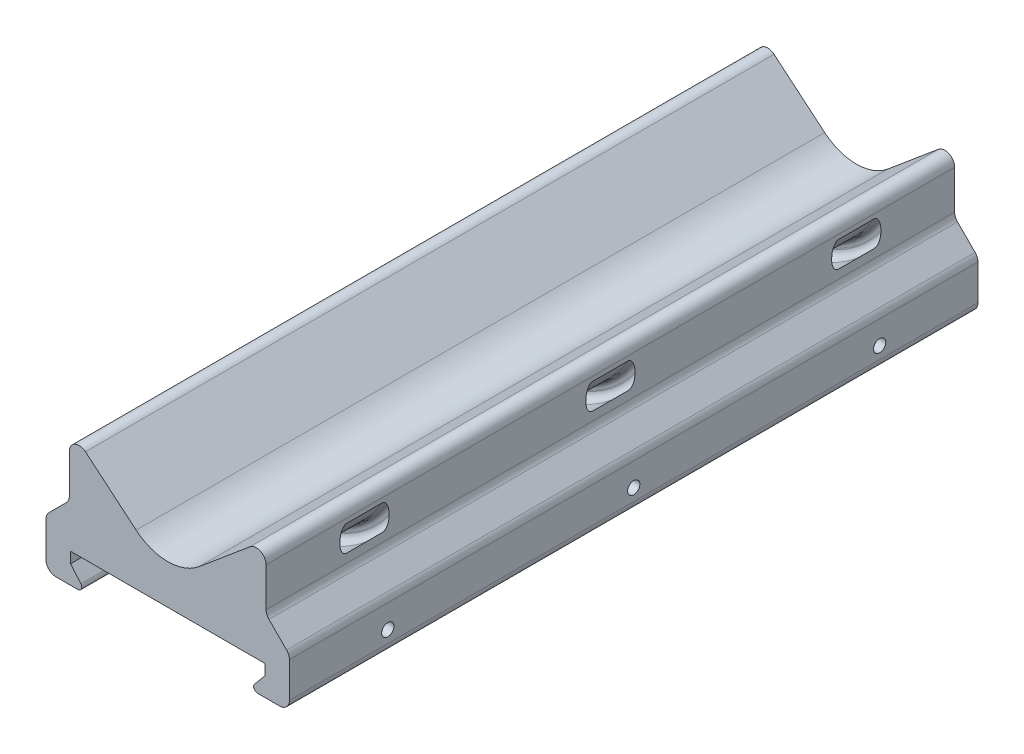
SolidWorks part; units mm, degrees
ref_plane "Front Plane" through (0, 0, 0) normal (0, 0, 1) x (1, 0, 0)
ref_plane "Top Plane" through (0, 0, 0) normal (0, 1, 0) x (1, 0, 0)
ref_plane "Right Plane" through (0, 0, 0) normal (1, 0, 0) x (0, 0, -1)
sketch "Sketch1" plane through (0, 0, 0) normal (0, 0, 1) x (1, 0, 0)
  line L0 (0, 15.6125) -> (0, -8.5333) construction
  line L1 (6.4279, 10.3936) -> (16.7144, 19.0251)
  line L2 (20, 17.493) -> (20, 9.5784)
  line L3 (20.5858, 8.1642) -> (24.1642, 4.5858)
  line L4 (24.75, 3.1716) -> (24.75, -4)
  line L5 (22.75, -6) -> (18.277, -6)
  line L7 (19.75, 0) -> (-19.75, 0)
  line L9 (-22.75, -6) -> (-18.277, -6)
  line L10 (-24.75, 3.1716) -> (-24.75, -4)
  line L11 (-20.5858, 8.1642) -> (-24.1642, 4.5858)
  line L12 (-20, 17.493) -> (-20, 9.5784)
  line L13 (-6.4279, 10.3936) -> (-16.7144, 19.0251)
  line L14 (-19.05, -0.1) -> (19.05, -0.1) construction
  line L15 (19.05, -0.1) -> (19.05, -2.1) construction
  line L16 (19.05, -2.1) -> (13.05, -8.1) construction
  line L17 (13.05, -8.1) -> (-13.05, -8.1) construction
  line L18 (-13.05, -8.1) -> (-19.05, -2.1) construction
  line L19 (-19.05, -0.1) -> (-19.05, -2.1) construction
  line L20 (17.6642, -4.6858) -> (19.75, -2.2)
  line L21 (19.75, -2.2) -> (19.75, 0)
  line L22 (-19.75, -2.2) -> (-19.75, 0)
  line L23 (-17.6642, -4.6858) -> (-19.75, -2.2)
  arc A0 (-6.4279, 10.3936) -> (6.4279, 10.3936) centre (0, 18.0541) ccw
  arc A1 (20, 9.5784) -> (20.5858, 8.1642) centre (22, 9.5784) ccw
  arc A2 (24.1642, 4.5858) -> (24.75, 3.1716) centre (22.75, 3.1716) cw
  arc A3 (24.75, -4) -> (22.75, -6) centre (22.75, -4) cw
  arc A4 (-22.75, -6) -> (-24.75, -4) centre (-22.75, -4) cw
  arc A5 (-24.75, 3.1716) -> (-24.1642, 4.5858) centre (-22.75, 3.1716) cw
  arc A6 (-20.5858, 8.1642) -> (-20, 9.5784) centre (-22, 9.5784) ccw
  arc A7 (16.7144, 19.0251) -> (20, 17.493) centre (18, 17.493) cw
  arc A8 (-20, 17.493) -> (-16.7144, 19.0251) centre (-18, 17.493) cw
  arc A9 (18.277, -6) -> (17.6642, -4.6858) centre (18.277, -5.2) cw
  arc A10 (-17.6642, -4.6858) -> (-18.277, -6) centre (-18.277, -5.2) cw
  point P11 (0, 0)
  point P19 (0, 5)
  point P22 (20, 8.75)
  point P25 (24.75, 4)
  point P28 (24.75, -6)
  point P31 (-24.75, -6)
  point P34 (-24.75, 4)
  point P37 (-20, 8.75)
  point P40 (20, 21.782)
  point P43 (-20, 21.782)
  point P51 (0, -8.1)
  point P52 (0, -0.1)
  point P56 (16.5614, -6)
  point P59 (-16.5614, -6)
  dimension "D10" = 10
  dimension "D11" = 2
  dimension "D18" = 0.8
  dimension "D1" = 19.75
  dimension "D2" = 5
  dimension "D3" = 20
  dimension "D4" = 135
  dimension "D5" = 50
  dimension "D6" = 6
  dimension "D7" = 4
  dimension "D8" = 50
  dimension "D9" = 5
  dimension "D12" = 38.1
  dimension "D13" = 135
  dimension "D14" = 8
  dimension "D15" = 2
  dimension "D16" = 0.2
  dimension "D17" = 2.2
extrude "Boss-Extrude1" add sketch "Sketch1" along normal blind 140
sketch "Sketch2" plane through (0, 0, 0) normal (1, 0, 0) x (0, 0, -1)
  line L0 (-140, 0) -> (0, 0) construction
  line L1 (-15, 5) -> (-25, 5)
  line L2 (-15, 5) -> (-15, 2)
  line L3 (-15, 2) -> (-25, 2)
  line L4 (-25, 5) -> (-25, 2)
  line L5 (0, 4.5858) -> (0, 8.1642) construction
  line L6 (-65, 5) -> (-75, 5)
  line L7 (-65, 5) -> (-65, 2)
  line L8 (-65, 2) -> (-75, 2)
  line L9 (-75, 5) -> (-75, 2)
  line L10 (-115, 5) -> (-125, 5)
  line L11 (-115, 5) -> (-115, 2)
  line L12 (-115, 2) -> (-125, 2)
  line L13 (-125, 5) -> (-125, 2)
  line L14 (-129.3538, 28.0541) -> (-44.4002, 28.0541) construction
  line L15 (-140, 8.0541) -> (0, 8.0541) construction
  dimension "D1" = 10
  dimension "D2" = 3
  dimension "D3" = 2
  dimension "D4" = 15
  dimension "D6" = 20
  dimension "D5" = 3
revolve "Cut-Revolve1" cut sketch "Sketch2" angle 360 about L14
hole_wizard "M3x0.5 Tapped Hole1" positions "Sketch3" profile "Sketch4" tap size "M3x0.5" standard "ANSI Metric" end condition through all
sketch "Sketch3" plane through (-24.75, 0, 0) normal (-1, 0, 0) x (0, 0, 1)
  line L0 (70, -1.5555) -> (20, -1.5555) construction
  line L1 (140, -6) -> (0, -6) construction
  point P0 (20, -1.5555)
  point P2 (70, -1.5555)
  point P12 (120, -1.5555)
  point P15 (0, 0)
  point P18 (0, 0)
  point P19 (70, -6)
  dimension "D1" = 50
  dimension "D3" = 50
sketch "Sketch4" plane through (-24.75, -1.5555, 20) normal (0, 1, 0) x (0, 0, 1)
  line L0 (0, 0) -> (0, 49.5)
  line L1 (0, 49.5) -> (1.25, 49.5)
  line L2 (1.25, 49.5) -> (1.25, 0.275)
  line L3 (1.25, 0.275) -> (1.525, 0)
  line L5 (1.525, 0) -> (0, 0)
  line L6 (-1.25, 0.275) -> (-1.525, 0) construction
  line L11 (0, -6.35) -> (0, 107.95) construction
  dimension "Thru Tap Drill Dia." = 2.5
  dimension "Thru Tap Drill Depth" = 49.5
  dimension "Near C'Sink Dia." = 3.05
  dimension "Near C'Sink Angle" = 90
cosmetic thread "Hole Thread2" parameters "D2"=3
cosmetic thread "Hole Thread3" parameters "D2"=3
cosmetic thread "Hole Thread4" parameters "D2"=3
fillet "Fillet2" radius 1.4 12 edges at (0, 2, 125) (0, 2, 115) (0, 5, 125) (0, 5, 115) (0, 2, 75) (0, 2, 65) (0, 5, 75) (0, 5, 65) (0, 2, 15) (0, 2, 25) (0, 5, 15) (0, 5, 25)
